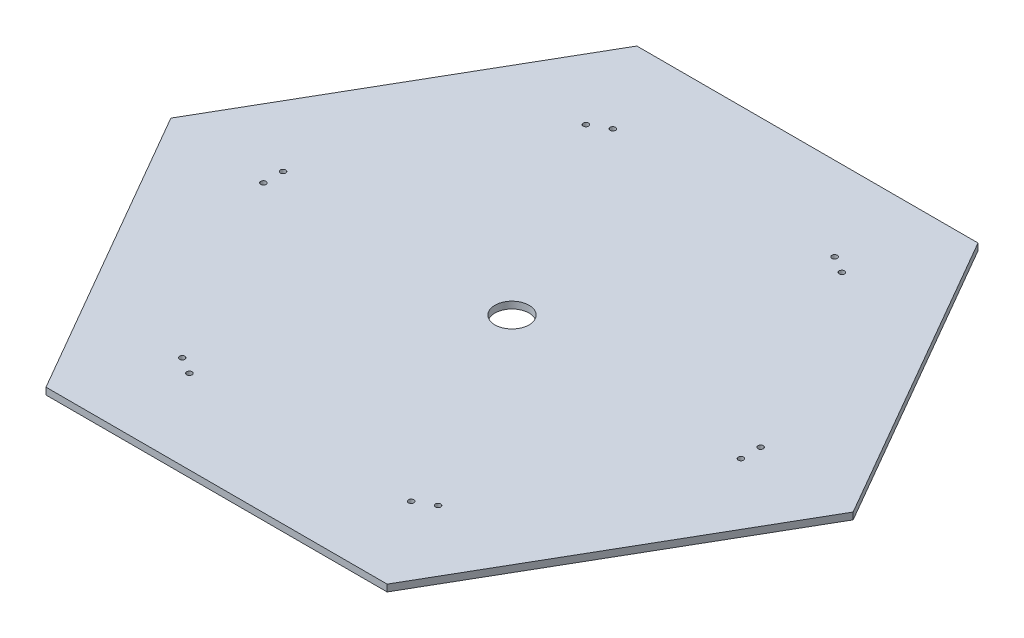
SolidWorks part; units mm, degrees
material "Ti-6Al-4VSolution treated and aged (SS)"
ref_plane "Front Plane" through (0, 0, 0) normal (0, 0, 1) x (1, 0, 0)
ref_plane "Top Plane" through (0, 0, 0) normal (0, 1, 0) x (1, 0, 0)
ref_plane "Right Plane" through (0, 0, 0) normal (1, 0, 0) x (0, 0, -1)
sketch "Sketch1" plane through (0, 0, 0) normal (0, 1, 0) x (1, 0, 0)
  line L1 (500, 0) -> (250, 433.0127)
  line L2 (250, 433.0127) -> (-250, 433.0127)
  line L3 (-250, 433.0127) -> (-500, 0)
  line L4 (-500, 0) -> (-250, -433.0127)
  line L5 (-250, -433.0127) -> (250, -433.0127)
  line L6 (250, -433.0127) -> (500, 0)
  circle A0 centre (0, 0) radius 433.0127 construction
  dimension "D1" = 500
extrude "Boss-Extrude1" add sketch "Sketch1" along normal blind 10
sketch "Sketch3" plane through (0, 0, 0) normal (0, -1, 0) x (1, 0, 0)
  line L0 (0, 0) -> (250, 433.0127) construction
  line L1 (162.4773, 310.3389) -> (187.5227, 295.8789) construction
  circle A0 centre (187.5227, 295.8789) radius 3.9687
  circle A1 centre (162.4773, 310.3389) radius 3.9687
  point P8 (175, 303.1089)
  dimension "D3" = 7.9375
  dimension "D1" = 14.46
  dimension "D2" = 150
extrude "Cut-Extrude1" cut sketch "Sketch3" against normal through all
sketch "Sketch4" plane through (0, 0, 0) normal (0, -1, 0) x (1, 0, 0)
  circle A0 centre (0, 0) radius 25
  dimension "D1" = 50
extrude "Cut-Extrude2" cut sketch "Sketch4" against normal through all
pattern_circular "CirPattern2" count 6 over 360 about axis through (0, 0, 0) along (0, 1, 0) of "Cut-Extrude1"
